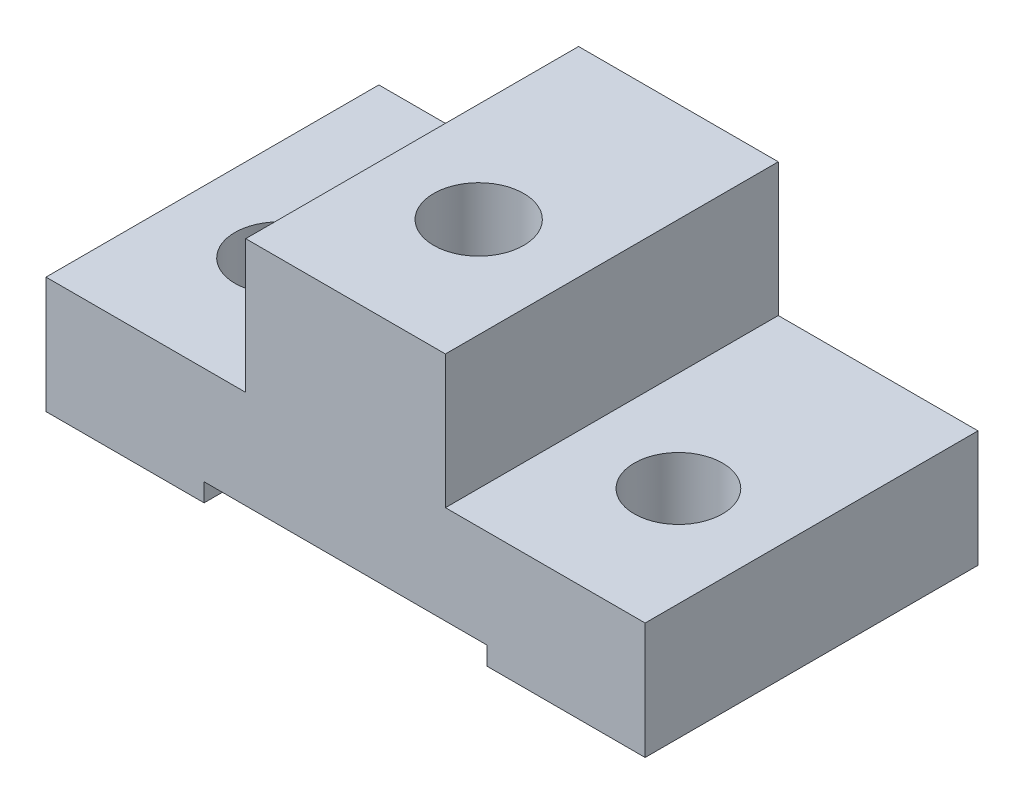
SolidWorks part; units mm, degrees
ref_plane "前视基准面" through (0, 0, 0) normal (0, 0, 1) x (1, 0, 0)
ref_plane "上视基准面" through (0, 0, 0) normal (0, 1, 0) x (1, 0, 0)
ref_plane "右视基准面" through (0, 0, 0) normal (1, 0, 0) x (0, 0, -1)
sketch "草图1" plane through (0, 0, 0) normal (0, 1, 0) x (1, 0, 0)
  line L1 (-18, -10) -> (18, -10)
  line L2 (-18, -10) -> (-18, 10)
  line L3 (-18, 10) -> (18, 10)
  line L4 (18, -10) -> (18, 10)
  line L5 (-18, -10) -> (18, 10) construction
  line L6 (-18, 10) -> (18, -10) construction
  point P0 (0, 0)
  dimension "D1" = 36
  dimension "D2" = 20
extrude "凸台-拉伸1" add sketch "草图1" along normal blind 15
sketch "草图2" plane through (0, 15, 0) normal (0, 1, 0) x (1, 0, 0)
  line L0 (-18, -10) -> (18, -10) construction
  line L1 (-18, 10) -> (-18, -10) construction
  line L2 (18, -10) -> (18, 10) construction
  circle A0 centre (-12, -2) radius 2.65
  circle A1 centre (12, -2) radius 2.65
  point P0 (-12, -2)
  point P1 (12, -2)
  dimension "D5" = 5.3
  dimension "D6" = 5.3
  dimension "D1" = 8
  dimension "D2" = 8
  dimension "D3" = 6
  dimension "D4" = 6
extrude "切除-拉伸1" cut sketch "草图2" against normal through all
sketch "草图3" plane through (0, 0, 10) normal (0, 0, 1) x (1, 0, 0)
  line L0 (-18, 0) -> (18, 0) construction
  line L1 (-18, 15) -> (-6, 15)
  line L2 (-18, 15) -> (-18, 7)
  line L3 (-18, 7) -> (-6, 7)
  line L4 (-6, 15) -> (-6, 7)
  line L5 (18, 15) -> (6, 15)
  line L6 (18, 15) -> (18, 7)
  line L7 (18, 7) -> (6, 7)
  line L8 (6, 15) -> (6, 7)
  line L9 (0, 0) -> (0, 16.3123) construction
  point P15 (0, 0)
  point P16 (0, 0)
  dimension "D1" = 7
  dimension "D2" = 7
  dimension "D3" = 12
  dimension "D4" = 12
extrude "切除-拉伸2" cut sketch "草图3" against normal through all contours L5 L8 L7 L6 | L2 L3 L4 L1
sketch "草图5" plane through (0, 0, 10) normal (0, 0, 1) x (1, 0, 0)
  line L0 (0, 0) -> (0, 14.2368) construction
  line L1 (-18, 0) -> (18, 0) construction
  line L2 (-8.5, 0) -> (8.5, 0)
  line L3 (-8.5, 0) -> (-8.5, 0.5)
  line L4 (-8.5, 0.5) -> (8.5, 0.5)
  line L5 (8.5, 0) -> (8.5, 0.5)
  point P10 (0, 0)
  dimension "D1" = 17
  dimension "D2" = 0.5
extrude "切除-拉伸3" cut sketch "草图5" against normal through all
sketch "草图6" plane through (0, 0.5, 0) normal (0, -1, 0) x (1, 0, 0)
  line L0 (8.5, -10) -> (8.5, 10) construction
  line L1 (-8.5, 10) -> (8.5, 10)
  line L2 (-8.5, 10) -> (-8.5, 8)
  line L3 (-8.5, 8) -> (8.5, 8)
  line L4 (8.5, 10) -> (8.5, 8)
  dimension "D1" = 17
  dimension "D2" = 2
extrude "切除-拉伸4" cut sketch "草图6" against normal blind 0.6
sketch "草图7" plane through (0, 0.5, 0) normal (0, -1, 0) x (1, 0, 0)
  line L0 (0, 11.2262) -> (0, -12.4653) construction
  line L1 (-12, 2) -> (12, 2) construction
  circle A0 centre (0, 2) radius 4.9
  point P7 (0, 2)
  dimension "D1" = 9.8
extrude "切除-拉伸5" cut sketch "草图7" against normal blind 0.8
sketch "草图8" plane through (0, 1.3, 0) normal (0, -1, 0) x (1, 0, 0)
  circle A0 centre (0, 2) radius 4
  point P0 (0, 2)
  dimension "D1" = 8
extrude "切除-拉伸6" cut sketch "草图8" against normal blind 5
sketch "草图9" plane through (0, 15, 0) normal (0, 1, 0) x (1, 0, 0)
  line L0 (-12, -2) -> (12, -2) construction
  line L1 (0, 11.1017) -> (0, -11.5325) construction
  point P7 (0, -2)
hole_wizard "1/4-28 螺纹孔1" positions "3D草图1" profile "草图10" tap size "1/4-28" standard "ANSI Inch"
sketch3d "3D草图1"
  point P0 (0, 15, 2)
sketch "草图10" plane through (0, 15, 2) normal (1, 0, 0) x (0, 0, 1)
  line L0 (0, 0) -> (0, 6.6254)
  line L1 (0, 6.6254) -> (2.7051, 5)
  line L2 (2.7051, 5) -> (2.7051, 0)
  line L5 (2.7051, 0) -> (0, 0)
  line L10 (0, 6.6254) -> (-2.7051, 5) construction
  line L11 (0, -6.35) -> (0, 107.95) construction
  dimension "螺纹孔钻头直径" = 5.4102
  dimension "螺纹孔钻头深度" = 5
  dimension "导头角度" = 118
cosmetic thread "孔螺蚊线1" parameters "D1"=5, "D2"=6.35
sketch "草图11" plane through (0, 6.3, 0) normal (0, -1, 0) x (1, 0, 0)
  circle A0 centre (0, 2) radius 0.5
  dimension "D1" = 1
extrude "切除-拉伸7" cut sketch "草图11" against normal through all
sketch "草图12" plane through (0, 0, -10) normal (0, 0, -1) x (-1, 0, 0)
  line L0 (0, 13.1431) -> (0, -4.2828) construction
  line L1 (-8.5, 0.5) -> (8.5, 0.5) construction
  point P4 (0, 4.7)
  dimension "D1" = 4.2
hole_wizard "1/4-28 螺纹孔3" positions "3D草图3" profile "草图14" tap size "1/4-28" standard "ANSI Inch"
sketch3d "3D草图3"
  point P0 (0, 4.7, -10)
sketch "草图14" plane through (0, 4.7, -10) normal (1, 0, 0) x (0, 1, 0)
  line L0 (0, 0) -> (0, 5.6254)
  line L1 (0, 5.6254) -> (2.7051, 4)
  line L2 (2.7051, 4) -> (2.7051, 0)
  line L5 (2.7051, 0) -> (0, 0)
  line L10 (0, 5.6254) -> (-2.7051, 4) construction
  line L11 (0, -6.35) -> (0, 107.95) construction
  dimension "螺纹孔钻头直径" = 5.4102
  dimension "螺纹孔钻头深度" = 4
  dimension "导头角度" = 118
cosmetic thread "孔螺蚊线3" parameters "D1"=4, "D2"=6.35
sketch "草图16" plane through (0, 0, -10) normal (0, 0, -1) x (-1, 0, 0)
  circle A0 centre (0, 4.7) radius 0.5
  dimension "D1" = 1
extrude "切除-拉伸8" cut sketch "草图16" against normal blind 10
